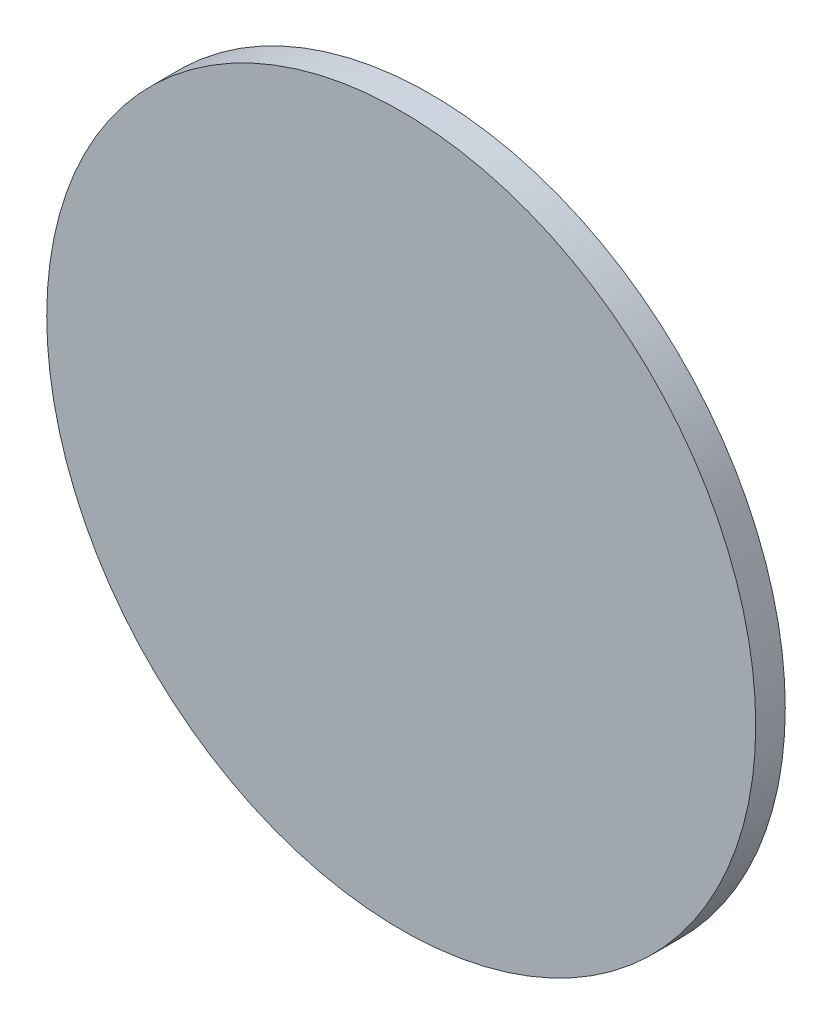
SolidWorks part; units mm, degrees
ref_plane "Front Plane" through (0, 0, 0) normal (0, 0, 1) x (1, 0, 0)
ref_plane "Top Plane" through (0, 0, 0) normal (0, 1, 0) x (1, 0, 0)
ref_plane "Right Plane" through (0, 0, 0) normal (1, 0, 0) x (0, 0, -1)
sketch "Sketch1" plane through (0, 0, 0) normal (0, 0, 1) x (1, 0, 0)
  circle A0 centre (0, 0) radius 38.1
  dimension "D1" = 76.2
extrude "Boss-Extrude1" add sketch "Sketch1" along normal mid plane 3.175
